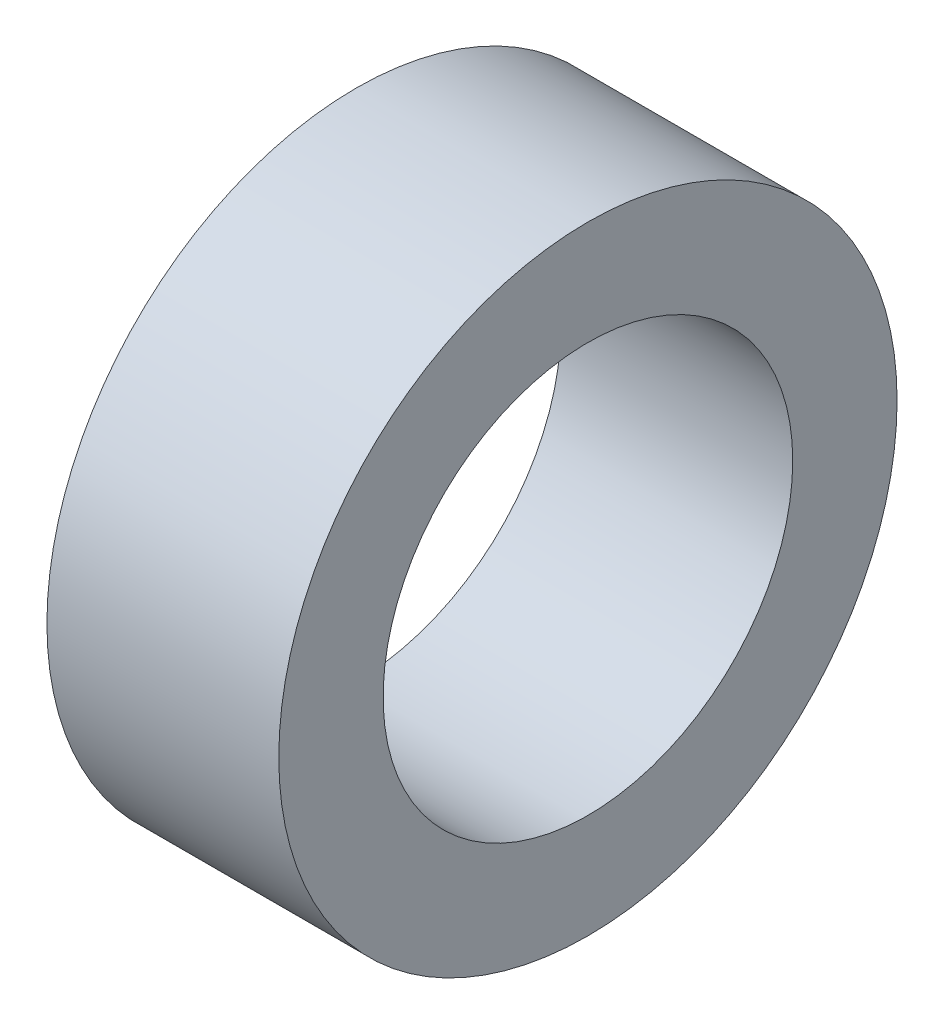
SolidWorks part; units mm, degrees
ref_plane "Front Plane" through (0, 0, 0) normal (0, 0, 1) x (1, 0, 0)
ref_plane "Top Plane" through (0, 0, 0) normal (0, 1, 0) x (1, 0, 0)
ref_plane "Right Plane" through (0, 0, 0) normal (1, 0, 0) x (0, 0, -1)
sketch "Sketch1" plane through (0, 0, 0) normal (1, 0, 0) x (0, 0, -1)
  circle A0 centre (0, 0) radius 2.65
  circle A1 centre (0, 0) radius 4
  dimension "D1" = 5.3
  dimension "D2" = 8
extrude "Boss-Extrude1" add sketch "Sketch1" along normal blind 3
